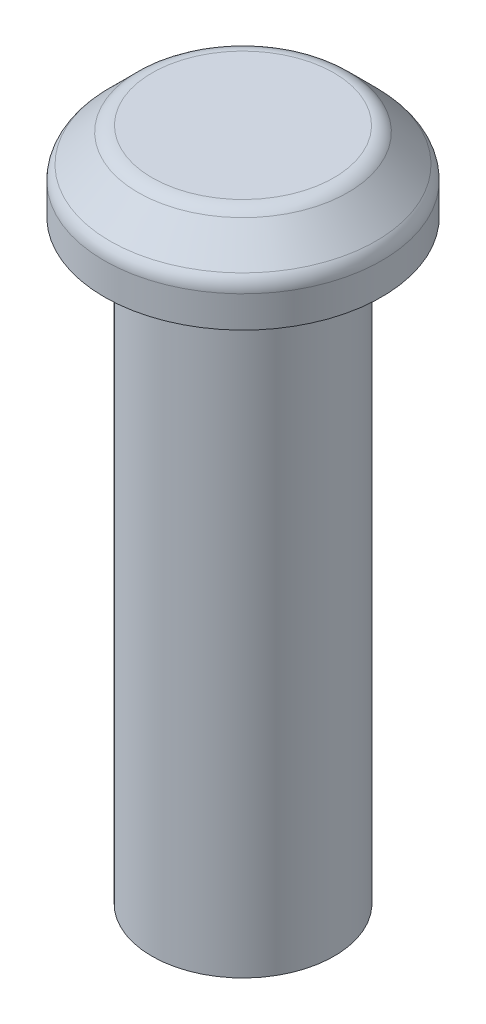
SolidWorks part; units mm, degrees
ref_plane "Front Plane" through (0, 0, 0) normal (0, 0, 1) x (1, 0, 0)
ref_plane "Top Plane" through (0, 0, 0) normal (0, 1, 0) x (1, 0, 0)
ref_plane "Right Plane" through (0, 0, 0) normal (1, 0, 0) x (0, 0, -1)
sketch "Sketch1" plane through (0, 0, 0) normal (0, 1, 0) x (1, 0, 0)
  circle A0 centre (0, 0) radius 2.3
  dimension "D1" = 4.6
extrude "Boss-Extrude1" add sketch "Sketch1" along normal blind 15
sketch "Sketch2" plane through (0, 15, 0) normal (0, 1, 0) x (1, 0, 0)
  circle A0 centre (0, 0) radius 3.5
  dimension "D1" = 7
extrude "Boss-Extrude2" add sketch "Sketch2" along normal blind 2
chamfer "Chamfer1" distance 1 angle 45 1 edges at (0, 17, 3.5)
fillet "Fillet1" radius 0.5 2 edges at (0, 17, 2.5) (0, 16, 3.5)
